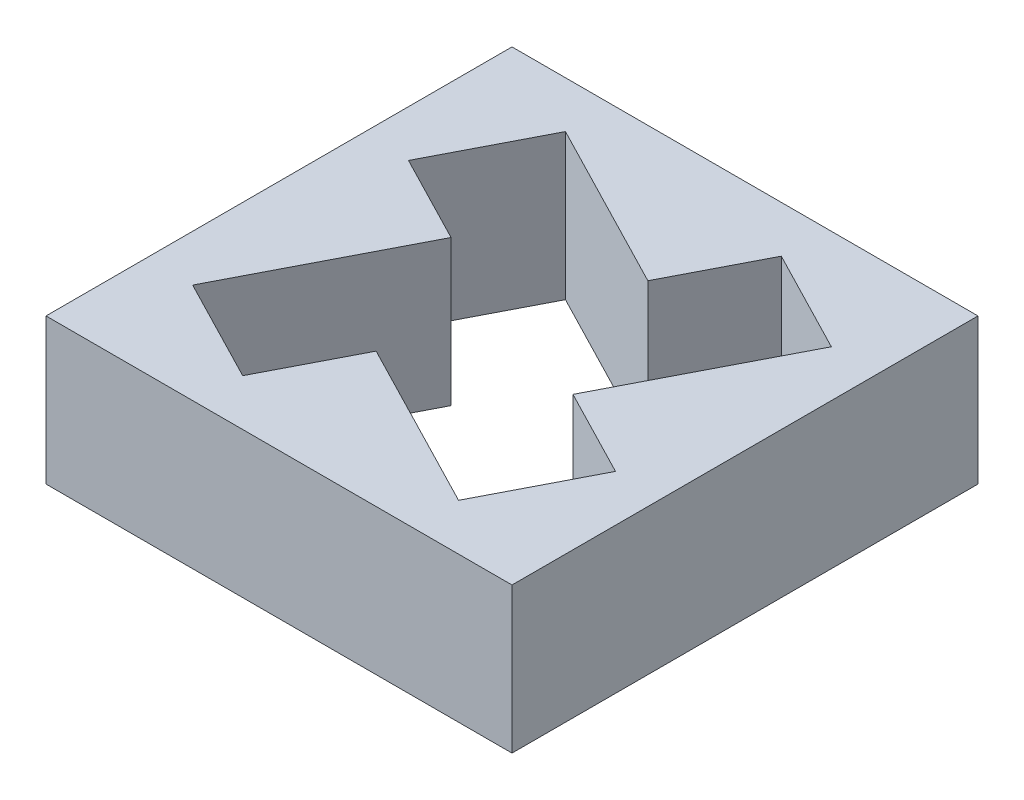
SolidWorks part; units mm, degrees
ref_plane "Front Plane" through (0, 0, 0) normal (0, 0, 1) x (1, 0, 0)
ref_plane "Top Plane" through (0, 0, 0) normal (0, 1, 0) x (1, 0, 0)
ref_plane "Right Plane" through (0, 0, 0) normal (1, 0, 0) x (0, 0, -1)
sketch "Sketch1" plane through (0, 0, 0) normal (0, 1, 0) x (1, 0, 0)
  line L1 (0, 0) -> (80, 0)
  line L2 (0, 0) -> (0, 80)
  line L3 (0, 80) -> (80, 80)
  line L4 (80, 0) -> (80, 80)
  dimension "D1" = 80
extrude "Boss-Extrude1" add sketch "Sketch1" along normal blind 25
sketch "Sketch2" plane through (0, 25, 0) normal (0, 1, 0) x (1, 0, 0)
  line L0 (72, 72) -> (72, 80) construction
  line L1 (8, 8) -> (72, 8)
  line L2 (8, 8) -> (8, 72)
  line L3 (8, 72) -> (72, 72)
  line L4 (72, 8) -> (72, 72)
  line L5 (80, 80) -> (0, 80) construction
  line L6 (72, 72) -> (80, 72) construction
  line L7 (80, 0) -> (80, 80) construction
  line L8 (8, 8) -> (8, 0) construction
  line L9 (0, 0) -> (80, 0) construction
  line L10 (8, 8) -> (0, 8) construction
  line L11 (0, 80) -> (0, 0) construction
  line L12 (8, 54.2292) -> (23.1052, 46.4296)
  line L13 (23.1052, 46.4296) -> (8, 17.176)
  line L14 (8, 17.176) -> (25.7708, 8)
  line L15 (25.7708, 8) -> (33.5704, 23.1052)
  line L16 (33.5704, 23.1052) -> (62.824, 8)
  line L17 (62.824, 8) -> (72, 25.7708)
  line L18 (72, 25.7708) -> (56.8948, 33.5704)
  line L19 (56.8948, 33.5704) -> (72, 62.824)
  line L20 (72, 62.824) -> (54.2292, 72)
  line L21 (54.2292, 72) -> (46.4296, 56.8948)
  line L22 (46.4296, 56.8948) -> (17.176, 72)
  line L23 (17.176, 72) -> (8, 54.2292)
  point P24 (8, 56.6165)
  point P29 (72, 66.3427)
  point P30 (72, 62.192)
  dimension "D1" = 8
  dimension "D2" = 20
  dimension "D3" = 17
extrude "Cut-Extrude1" cut sketch "Sketch2" against normal through all contours L22 L23 L12 L13 L14 L15 L16 L17 L18 L19 L20 L21
